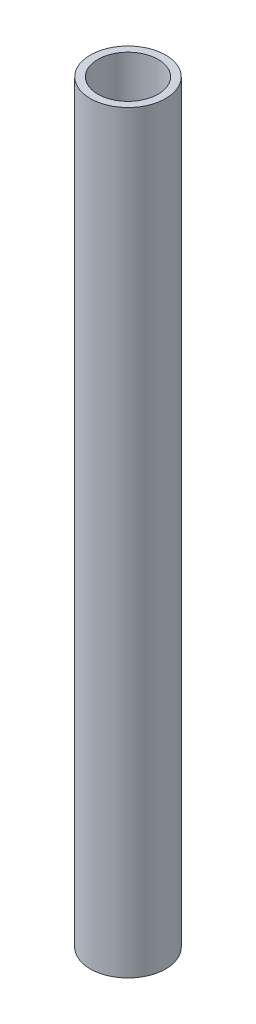
SolidWorks part; units mm, degrees
ref_plane "Front Plane" through (0, 0, 0) normal (0, 0, 1) x (1, 0, 0)
ref_plane "Top Plane" through (0, 0, 0) normal (0, 1, 0) x (1, 0, 0)
ref_plane "Right Plane" through (0, 0, 0) normal (1, 0, 0) x (0, 0, -1)
sketch "Sketch1" plane through (0, 0, 0) normal (0, 1, 0) x (1, 0, 0)
  circle A0 centre (0, 0) radius 50
  circle A1 centre (0, 0) radius 40
  dimension "D1" = 100
  dimension "D2" = 80
extrude "Boss-Extrude1" add sketch "Sketch1" along normal blind 1000
